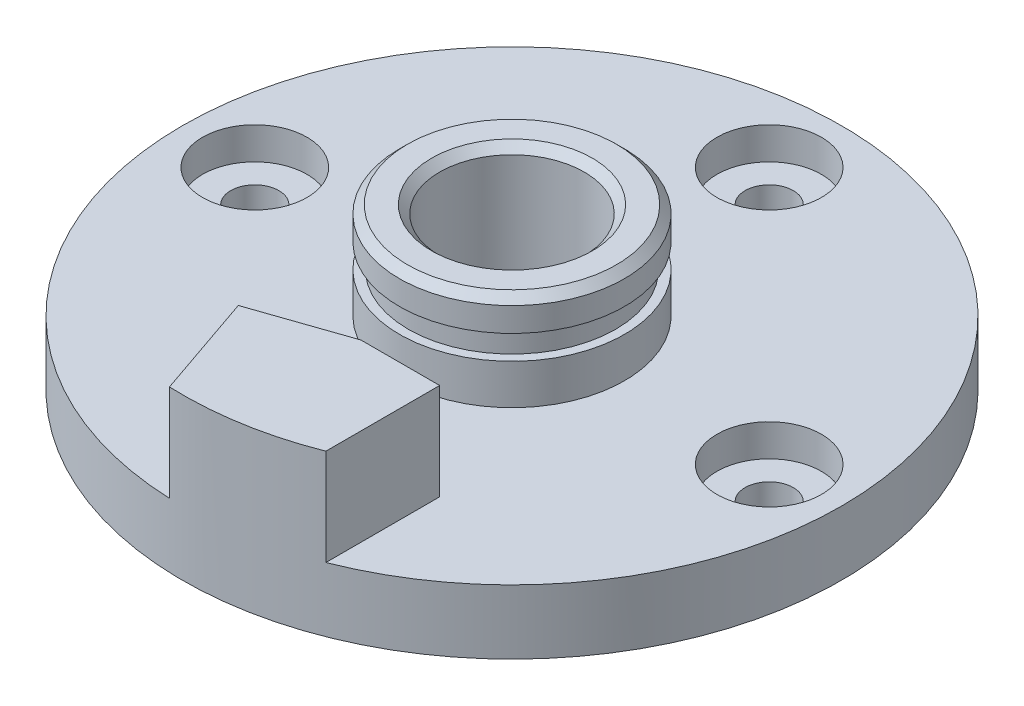
SolidWorks part; units mm, degrees
ref_plane "前视基准面" through (0, 0, 0) normal (0, 0, 1) x (1, 0, 0)
ref_plane "上视基准面" through (0, 0, 0) normal (0, 1, 0) x (1, 0, 0)
ref_plane "右视基准面" through (0, 0, 0) normal (1, 0, 0) x (0, 0, -1)
sketch "草图1" plane through (0, 0, 0) normal (0, 0, 1) x (1, 0, 0)
  line L18 (-4.5, 0) -> (-20.5, 0)
  line L19 (-20.5, 0) -> (-20.5, 4)
  line L20 (-20.5, 4) -> (-7, 4)
  line L21 (-7, 4) -> (-7, 6.5)
  line L22 (-7, 10) -> (-4.5, 10)
  line L23 (0, 7) -> (0, 0) construction
  line L24 (-4.5, 0) -> (-4.5, 10)
  line L25 (-7, 6.5) -> (-6.45, 6.5)
  line L26 (-6.45, 6.5) -> (-6.45, 8)
  line L27 (-6.45, 8) -> (-7, 8)
  line L28 (-7, 8) -> (-7, 10)
  point P0 (0, 0)
  point P6 (0, 0)
  point P11 (0, 0)
  dimension "D1" = 2.5
  dimension "D2" = 1.5
  dimension "D3" = 4.5
  dimension "D4" = 16
  dimension "D5" = 0.55
  dimension "D6" = 2.5
  dimension "D7" = 4
  dimension "D9" = 6
revolve "旋转1" add sketch "草图1" angle 360 about L23
sketch "草图2" plane through (0, 0, 0) normal (0, 1, 0) x (1, 0, 0)
  line L0 (0, 16) -> (0, -16) construction
  line L1 (-16, 0) -> (16, 0) construction
  circle A0 centre (0, 0) radius 16 construction
  circle A1 centre (-16, 0) radius 1.5
  circle A2 centre (0, 16) radius 1.5
  circle A4 centre (16, 0) radius 1.5
  dimension "D1" = 32
extrude "切除-拉伸1" cut sketch "草图2" along normal through all
sketch "草图3" plane through (0, 0, 0) normal (0, 1, 0) x (1, 0, 0)
  circle A0 centre (-16, 0) radius 3.25
  circle A2 centre (0, 16) radius 3.25
  circle A3 centre (16, 0) radius 3.25
  dimension "D1" = 6.5
  dimension "D2" = 6.5
  dimension "D3" = 6.5
extrude "切除-拉伸2" cut sketch "草图3" against normal blind 2 from surface at 4 starting at face at (-17.5, 4, 0)
sketch "草图4" plane through (0, 4, 0) normal (0, 1, 0) x (1, 0, 0)
  line L1 (7.5, -12) -> (-7.5, -12)
  line L2 (7.5, -12) -> (7.5, -19.0788)
  line L4 (-7.5, -12) -> (-7.5, -19.0788)
  circle A0 centre (0, 0) radius 20.5 construction
  arc A2 (7.5, -19.0788) -> (-7.5, -19.0788) centre (0, 0) cw
  circle A4 centre (0, 0) radius 4.5 construction
  dimension "D3" = 7.5
  dimension "D1" = 15
  dimension "D2" = 12
extrude "凸台-拉伸1" add sketch "草图4" along normal blind 6
sketch "草图5" plane through (0, 0, 0) normal (0, -1, 0) x (1, 0, 0)
  circle A0 centre (0, 0) radius 7.5
  dimension "15" = 15
extrude "切除-拉伸3" cut sketch "草图5" against normal blind 1
chamfer "倒角1" distance 0.5 angle 45 2 edges at (-4.5, 10, 0) (4.5, 1, 0)
chamfer "倒角2" distance 0.5 angle 45 1 edges at (-7, 10, 0)
sketch "草图6" plane through (0, 10, 0) normal (0, 1, 0) x (1, 0, 0)
  line L0 (2.6, -12) -> (-1.9677, -14.0337)
  line L1 (7.5, -19.0788) -> (7.5, -12) construction
  line L2 (-1.9677, -14.0337) -> (1.2963, -21.3647)
  line L3 (2.6, -12) -> (-7.5, -12)
  line L4 (-7.5, -12) -> (-7.5, -20.0624)
  line L5 (1.2963, -21.3647) -> (-7.5, -20.0624)
  line L6 (7.5, -12) -> (-7.5, -12) construction
  dimension "D1" = 5
  dimension "D2" = 4.9
  dimension "D3" = 24
extrude "切除-拉伸6" cut sketch "草图6" against normal blind 6 contours L2 L5 L4 L3 L0
sketch "草图7" plane through (0, 4, 0) normal (0, 1, 0) x (1, 0, 0)
  line L0 (2.6, -12) -> (-3.0731, -13.9534)
  line L1 (-3.0731, -13.9534) -> (-0.8247, -20.4834)
  line L2 (2.6, -12) -> (-1.9677, -14.0337)
  line L3 (-1.9677, -14.0337) -> (0.9024, -20.4801)
  arc A0 (7.5, -19.0788) -> (0.9024, -20.4801) centre (0, 0) ccw construction
  arc A2 (-0.8247, -20.4834) -> (0.9024, -20.4801) centre (0, 0) ccw
  dimension "D1" = 6
  dimension "D2" = 5
extrude "凸台-拉伸2" add sketch "草图7" along normal blind 6 contours L1 A2 L3 L2 L0
